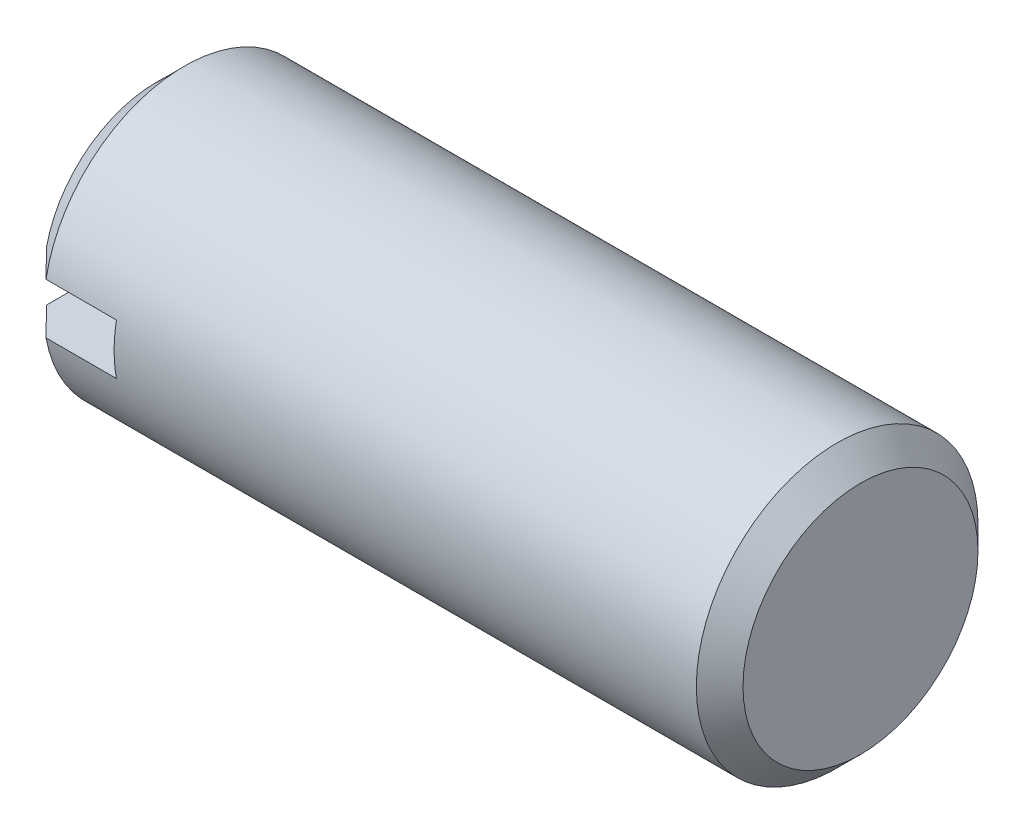
SolidWorks part; units mm, degrees
ref_plane "Plane1" through (0, 0, 0) normal (0, 0, 1) x (1, 0, 0)
ref_plane "Plane2" through (0, 0, 0) normal (0, 1, 0) x (1, 0, 0)
ref_plane "Plane3" through (0, 0, 0) normal (1, 0, 0) x (0, 0, -1)
sketch "BodySke" plane through (0, 0, 0) normal (0, 0, 1) x (1, 0, 0)
  line L0 (0, 0) -> (0, 4)
  line L1 (0, 4) -> (1, 5)
  line L3 (1, 5) -> (24.172, 5)
  line L4 (25, 4.172) -> (25, 0)
  line L5 (25, 0) -> (0, 0)
  line L6 (-3.6761, 0) -> (29.1174, 0) construction
  line L8 (25, 4.172) -> (24.172, 5)
  line L10 (25, -4.172) -> (24.172, -5) construction
  line L11 (1.5, 4.525) -> (1.5, -1.825) construction
  line L12 (13, 4.525) -> (13, -1.825) construction
  line L13 (9, 4.525) -> (9, -1.825) construction
  dimension "Body_ch_ang" = 45
  dimension "Diameter" = 10
  dimension "Minor_dia" = 8.344
  dimension "Thread_nom" = 12
  dimension "Thread_length" = 16
  dimension "Length" = 25
  dimension "D2" = 45
  dimension "Advance" = 1.5
  dimension "D4" = 4
revolve "Base-Revolve" add sketch "BodySke"
cosmetic thread "ThreadCosmetic" [suppressed]
extrude "Slot" cut sketch "SlotSke" against normal through all and the other way through all
sketch "SlotSke" plane through (0, 0, 0) normal (0, 0, 1) x (1, 0, 0)
  line L1 (-0.9887, 0) -> (5.0854, 0) construction
  line L2 (-3.6761, 0) -> (29.1174, 0) construction
  line L3 (0, 4) -> (0, -4) construction
  line L4 (0, 0.9) -> (3.5, 0.9)
  line L5 (0, 0.9) -> (0, -0.9)
  line L6 (0, -0.9) -> (3.5, -0.9)
  line L7 (3.5, 0.9) -> (3.5, -0.9)
  dimension "Slot_wid" = 1.8
  dimension "Slot_Dep" = 3.5
sketch "ThdSchSke" plane through (0, 0, 0) normal (0, 0, 1) x (1, 0, 0)
  line L0 (13, -4.172) -> (12.4202, -5)
  line L1 (13, -4.172) -> (13.5798, -5)
  line L2 (13.5798, -5) -> (13.5798, -6.25)
  line L3 (-3.175, 0) -> (5.1513, 0) construction
  line L5 (13.5798, -6.25) -> (12.4202, -6.25)
  line L6 (12.4202, -6.25) -> (12.4202, -5)
  dimension "Thread_minor" = 8.344
  dimension "Diameter" = 10
  dimension "SideAngle" = 55
  dimension "VeeAngle" = 70
  dimension "Overcut" = 12.5
  dimension "Start" = 13
revolve "ThreadSchematic" [suppressed] cut sketch "ThdSchSke" angle 360 about L3
pattern_linear "ThdSchPat" [suppressed]
equation "\"Thread_minor@ThreadCosmetic\"  =  \"Minor_dia@BodySke\""
equation "\"D4@BodySke\" = \"Diameter@BodySke\" * 0.4"
equation "\"Thread_length@ThreadCosmetic\" = ((sgn( (\"Length@BodySke\" - \"Advance@BodySke\" * 1.5  ) - \"Thread_nom@BodySke\" )-1)*( (\"Length@BodySke\" - \"Advance@BodySke\" * 1.5 ) - \"Thread_nom@BodySke\" ))/-2+ \"Thread_nom@BodySke\""
equation "\"Thread_minor@ThdSchSke\" = \"Minor_dia@BodySke\""
equation "\"Diameter@ThdSchSke\" = \"Diameter@BodySke\""
equation "\"Overcut@ThdSchSke\" = \"Diameter@BodySke\" * 1.25"
equation "\"Start@ThdSchSke\" = 0.000001 + \"Length@BodySke\" - \"Thread_length@ThreadCosmetic\"  '---Countersunk---"
equation "\"Num_threads@ThdSchPat\" = int( \"Thread_length@ThreadCosmetic\" / \"Advance@BodySke\" + 0.999 )  + 1"
equation "\"Advance@ThdSchPat\" = \"Thread_length@ThreadCosmetic\" /  (\"Num_threads@ThdSchPat\" - 1) 'relax it"
equation "\"Num_threads@ThdSchPat\" = \"Num_threads@ThdSchPat\" - sgn( \"Num_threads@ThdSchPat\" - 1) '---chamfered tips only---"
